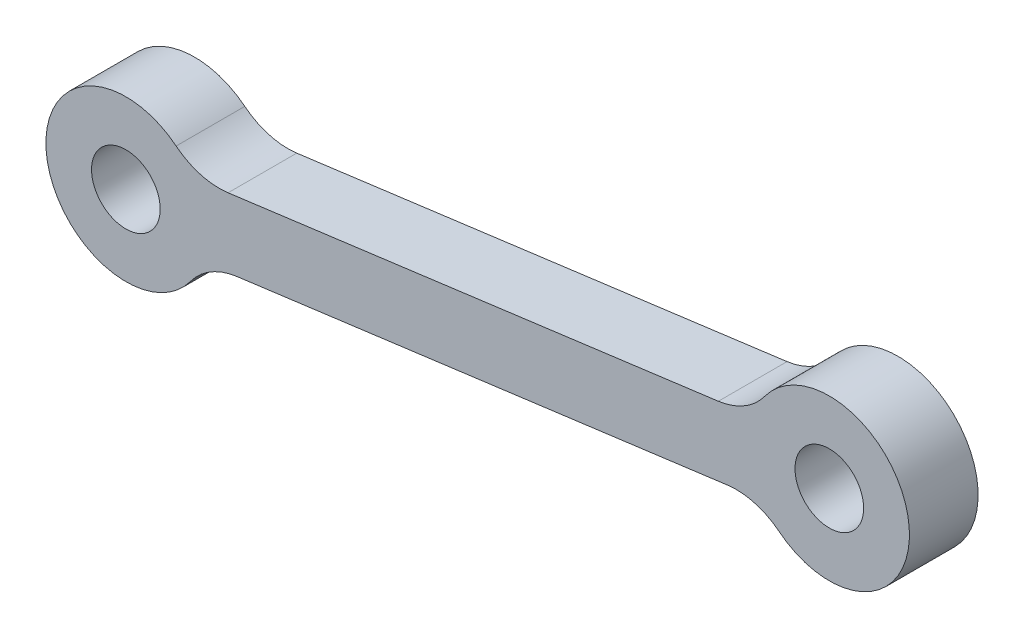
SolidWorks part; units mm, degrees
ref_plane "Front Plane" through (0, 0, 0) normal (0, 0, 1) x (1, 0, 0)
ref_plane "Top Plane" through (0, 0, 0) normal (0, 1, 0) x (1, 0, 0)
ref_plane "Right Plane" through (0, 0, 0) normal (1, 0, 0) x (0, 0, -1)
sketch "Sketch1" plane through (0, 0, 0) normal (0, 0, 1) x (1, 0, 0)
  line L0 (0, 0) -> (30.73, 4.05) construction
  line L1 (-6, 0) -> (6, 0) construction
  line L2 (0, 0) -> (0.1958, 1.4872) construction
  line L3 (0, 0) -> (-0.1958, 1.4872) construction
  line L4 (0, 0) -> (2.7835, 2.1358) construction
  line L5 (9, 0) -> (20.4112, 0) construction
  line L6 (2.9485, 1.9016) -> (27.3988, 5.1239)
  line L7 (3.3364, -1.0733) -> (27.7908, 2.1497)
  line L8 (0.0067, 0.0052) -> (3.3436, 1.0613) construction
  line L10 (0, 1.5) -> (0, -3.4948) construction
  line L23 (0.0067, 0.0052) -> (6.2485, 0.827) construction
  circle A2 centre (0, 0) radius 1.5
  arc A7 (3.4773, 0.4583) -> (3.4768, 0.462) centre (0.0067, 0.0052) ccw
  arc A27 (2.9485, 1.9016) -> (3.3364, -1.0733) centre (0.0067, 0.0052) ccw
  circle A41 centre (30.73, 4.05) radius 1.5
  arc A44 (27.7908, 2.1497) -> (27.3988, 5.1239) centre (30.73, 4.05) ccw
  dimension "D3" = 3
  dimension "D5" = 1.5
  dimension "D7" = 37.5
  dimension "D20" = 3
  dimension "D23" = 7
  dimension "D18" = 7.5
  dimension "D22" = 4.05
extrude "Boss-Extrude1" add sketch "Sketch1" against normal blind 3
fillet "Fillet1" radius 3 4 edges at (27.7908, 2.1497, -1.5) (27.3988, 5.1239, -1.5) (3.3364, -1.0733, -1.5) (2.9485, 1.9016, -1.5)
scale "Scale1" scale about centroid uniform scaling yes scale factor 1.9
